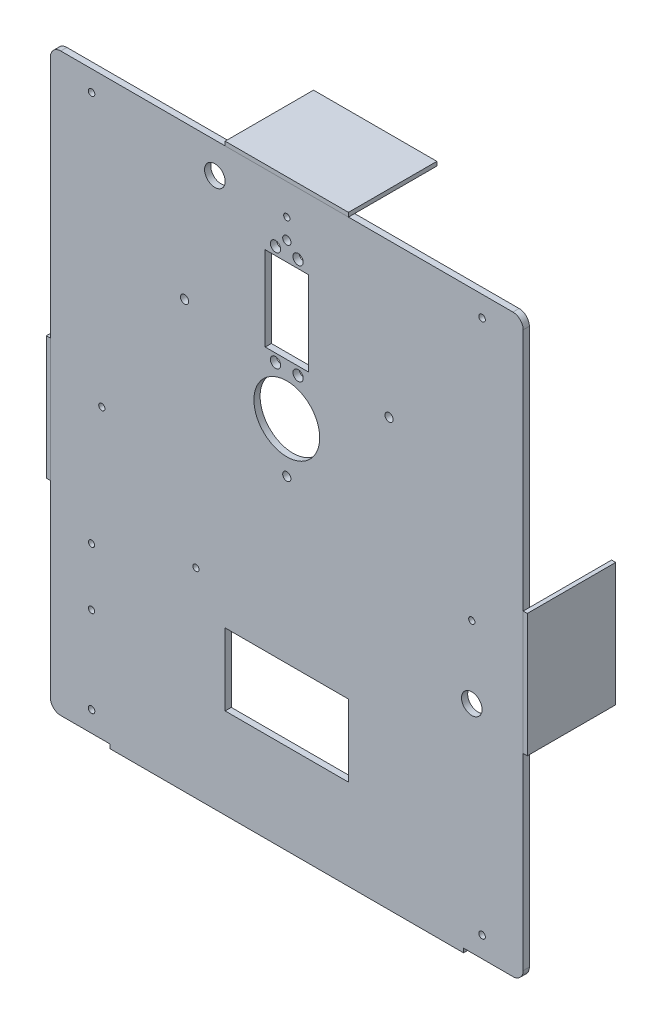
SolidWorks part; units mm, degrees
ref_plane "前视基准面" through (0, 0, 0) normal (0, 0, 1) x (1, 0, 0)
ref_plane "上视基准面" through (0, 0, 0) normal (0, 1, 0) x (1, 0, 0)
ref_plane "右视基准面" through (0, 0, 0) normal (1, 0, 0) x (0, 0, -1)
sketch "草图1" plane through (0, 0, 0) normal (0, 0, 1) x (1, 0, 0)
  line L1 (105, -140) -> (-105, -140)
  line L2 (115, -130) -> (115, 130)
  line L3 (105, 140) -> (-105, 140)
  line L4 (-115, -130) -> (-115, 130)
  line L5 (115, -140) -> (-115, 140) construction
  line L6 (115, 140) -> (-115, -140) construction
  line L10 (0, 0) -> (0, 50000) construction
  line L11 (0, 65.5) -> (0, 115.25) construction
  line L12 (-1000, 65.5) -> (49000, 65.5) construction
  line L13 (-115, 135) -> (-115, 130)
  line L14 (-105, 140) -> (-110, 140)
  line L15 (105, 140) -> (110, 140)
  line L16 (115, 135) -> (115, 130)
  line L17 (115, -135) -> (115, -130)
  line L18 (105, -140) -> (110, -140)
  line L19 (-115, -130) -> (-115, -135)
  line L20 (-110, -140) -> (-105, -140)
  line L21 (0, 85.5) -> (-50000, 85.5) construction
  line L22 (10.5, 65) -> (-10.5, 65)
  line L23 (10.5, 65) -> (10.5, 106)
  line L24 (10.5, 106) -> (-10.5, 106)
  line L25 (-10.5, 65) -> (-10.5, 106)
  line L26 (10.5, 65) -> (-10.5, 106) construction
  line L27 (10.5, 106) -> (-10.5, 65) construction
  line L29 (30, -98.0728) -> (-30, -98.0728)
  line L30 (30, -98.0728) -> (30, -63.0728)
  line L31 (30, -63.0728) -> (-30, -63.0728)
  line L32 (-30, -98.0728) -> (-30, -63.0728)
  line L33 (30, -98.0728) -> (-30, -63.0728) construction
  line L34 (30, -63.0728) -> (-30, -98.0728) construction
  circle A0 centre (0, 115.25) radius 2
  circle A2 centre (0, 65.5) radius 49.75 construction
  circle A3 centre (-49.75, 65.5) radius 2
  circle A4 centre (0, 15.75) radius 2
  circle A5 centre (49.75, 65.5) radius 2
  circle A7 centre (-95, -130) radius 1.6
  circle A8 centre (95, -130) radius 1.6
  circle A9 centre (-95, 130) radius 1.6
  circle A10 centre (95, 130) radius 1.6
  arc A11 (-115, 135) -> (-110, 140) centre (-110, 135) cw
  arc A12 (110, 140) -> (115, 135) centre (110, 135) cw
  arc A13 (115, -135) -> (110, -140) centre (110, -135) cw
  arc A14 (-115, -135) -> (-110, -140) centre (-110, -135) ccw
  circle A17 centre (-5.5, 61.05) radius 2.5
  circle A18 centre (5.5, 61.05) radius 2.5
  circle A19 centre (5.5, 109.95) radius 2.5
  circle A20 centre (-5.5, 109.95) radius 2.5
  circle A21 centre (0, 40) radius 16
  circle A22 centre (-95, -87.9581) radius 1.5
  circle A23 centre (-95, -60.0581) radius 1.5
  circle A24 centre (-44.2, -44.8581) radius 1.5
  circle A25 centre (-90, 0) radius 1.51
  circle A26 centre (90, 0) radius 1.51
  circle A27 centre (0, 125) radius 1.51
  circle A28 centre (-35, 125) radius 5
  circle A29 centre (90, -35) radius 5
  point P0 (0, 0)
  point P30 (0, -80.5728)
  point P51 (0, 85.5)
  point P70 (0, 65)
  dimension "D3" = 20
  dimension "D9" = 60
  dimension "D10" = 10
  dimension "D12" = 10
  dimension "D14" = 20
  dimension "D16" = 10
  dimension "D18" = 5
  dimension "D19" = 5
  dimension "D20" = 5
  dimension "D21" = 5
  dimension "D25" = 3.95
  dimension "D29" = 35
  dimension "D30" = 25
  dimension "D31" = 27.9
  dimension "D32" = 50.8
  dimension "D34" = 25
  dimension "D35" = 15
  dimension "D37" = 15
  dimension "D39" = 35
  dimension "D1" = 280
  dimension "D2" = 230
  dimension "D4" = 49.75
  dimension "D11" = 20
  dimension "D13" = 20
  dimension "D15" = 10
  dimension "D17" = 20
  dimension "D22" = 21
  dimension "D23" = 41
  dimension "D24" = 75
  dimension "D26" = 3.95
  dimension "D27" = 5
  dimension "D28" = 5
  dimension "D33" = 15.2
  dimension "D36" = 9.75
  dimension "D38" = 35
extrude "凸台-拉伸1" add sketch "草图1" along normal blind 3
sketch "草图2" plane through (0, 0, 3) normal (0, 0, 1) x (1, 0, 0)
  line L0 (-115, 135) -> (-115, -135) construction
  line L1 (-115, 16.5082) -> (-117, 16.5082)
  line L2 (-115, 16.5082) -> (-115, -43.4918)
  line L3 (-115, -43.4918) -> (-117, -43.4918)
  line L4 (-117, 16.5082) -> (-117, -43.4918)
  line L5 (0, -1000) -> (0, 49000) construction
  line L6 (115, -43.4918) -> (117, -43.4918)
  line L7 (115, 16.5082) -> (115, -43.4918)
  line L8 (115, 16.5082) -> (117, 16.5082)
  line L9 (117, 16.5082) -> (117, -43.4918)
  line L10 (110, 140) -> (-110, 140) construction
  line L11 (-30, 140) -> (30, 140)
  line L12 (-30, 140) -> (-30, 142)
  line L13 (-30, 142) -> (30, 142)
  line L14 (30, 140) -> (30, 142)
  line L15 (-1000, 0) -> (49000, 0) construction
  point P6 (-115, -13.4918)
  point P20 (0, 140)
  dimension "D1" = 30
  dimension "D2" = 60
  dimension "D3" = 2
  dimension "D4" = 60
  dimension "D5" = 30
  dimension "D6" = 2
extrude "凸台-拉伸2" add sketch "草图2" against normal blind 43 separate body
sketch "草图3" plane through (0, 0, 3) normal (0, 0, 1) x (1, 0, 0)
  line L0 (-110, -140) -> (110, -140) construction
  line L1 (-86, -140) -> (86, -140)
  line L2 (-86, -140) -> (-86, -142)
  line L3 (-86, -142) -> (86, -142)
  line L4 (86, -140) -> (86, -142)
  line L5 (0, -1000) -> (0, 49000) construction
  point P6 (0, -140)
  dimension "D1" = 86
  dimension "D2" = 86
  dimension "D3" = 2
extrude "凸台-拉伸3" add sketch "草图3" against normal blind 13
